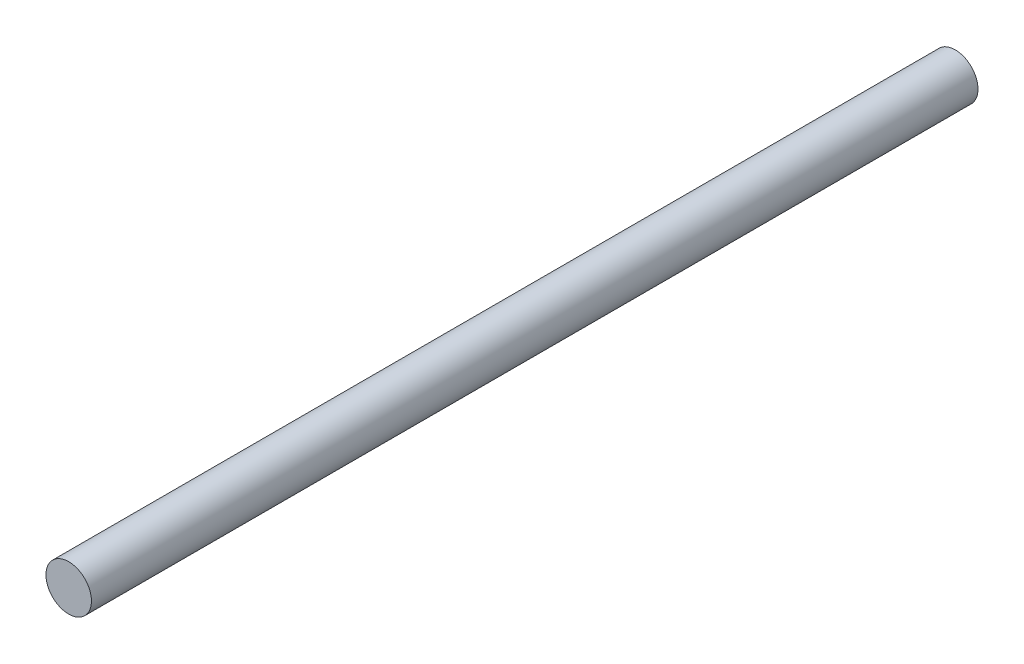
SolidWorks part; units mm, degrees
ref_plane "Front Plane" through (0, 0, 0) normal (0, 0, 1) x (1, 0, 0)
ref_plane "Top Plane" through (0, 0, 0) normal (0, 1, 0) x (1, 0, 0)
ref_plane "Right Plane" through (0, 0, 0) normal (1, 0, 0) x (0, 0, -1)
sketch "Sketch1" plane through (0, 0, 0) normal (0, 0, 1) x (1, 0, 0)
  circle A0 centre (0, 0) radius 10
  dimension "D1" = 20
extrude "Boss-Extrude1" add sketch "Sketch1" against normal blind 390
